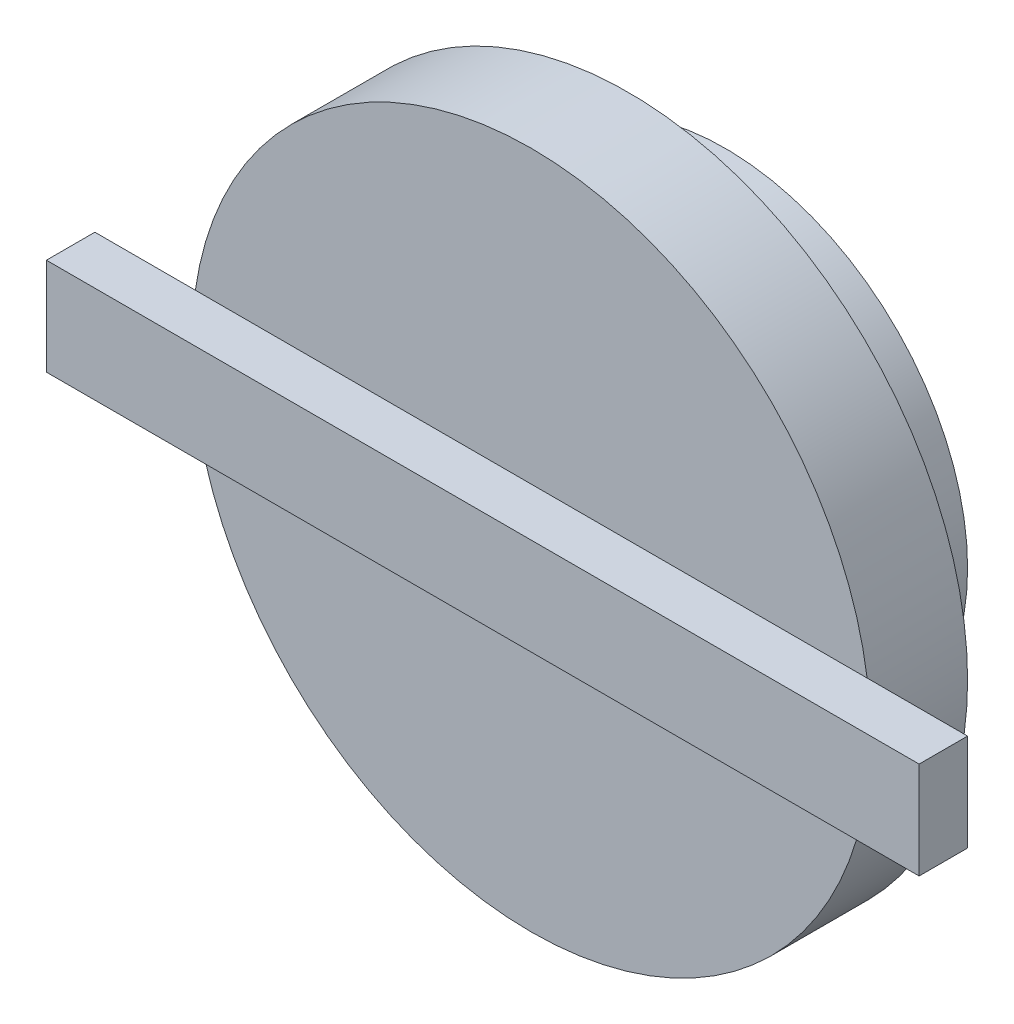
SolidWorks part; units mm, degrees
ref_plane "Front Plane" through (0, 0, 0) normal (0, 0, 1) x (1, 0, 0)
ref_plane "Top Plane" through (0, 0, 0) normal (0, 1, 0) x (1, 0, 0)
ref_plane "Right Plane" through (0, 0, 0) normal (1, 0, 0) x (0, 0, -1)
sketch "Sketch1" plane through (0, 0, 0) normal (0, 0, 1) x (1, 0, 0)
  circle A0 centre (0, 0) radius 25
  dimension "D1" = 50
extrude "Boss-Extrude1" add sketch "Sketch1" along normal blind 10
sketch "Sketch3" plane through (0, 0, 10) normal (0, 0, 1) x (1, 0, 0)
  circle A0 centre (0, 0) radius 35
extrude "Boss-Extrude2" add sketch "Sketch3" along normal blind 10
sketch "Sketch4" plane through (0, 0, 20) normal (0, 0, 1) x (1, 0, 0)
  line L1 (-45, -5) -> (45, -5)
  line L2 (-45, -5) -> (-45, 5)
  line L3 (-45, 5) -> (45, 5)
  line L4 (45, -5) -> (45, 5)
  line L5 (-45, -5) -> (45, 5) construction
  line L6 (-45, 5) -> (45, -5) construction
  point P0 (0, 0)
  dimension "D1" = 10
  dimension "D2" = 90
extrude "Boss-Extrude3" add sketch "Sketch4" along normal blind 5
sketch "Sketch6" plane through (0, 0, 25) normal (0, 0, 1) x (1, 0, 0)
  line L0 (-45, 0) -> (45, 0) construction
  line L1 (-45, 5) -> (-45, -5) construction
  line L2 (45, -5) -> (45, 5) construction
  point P6 (0, 0)
